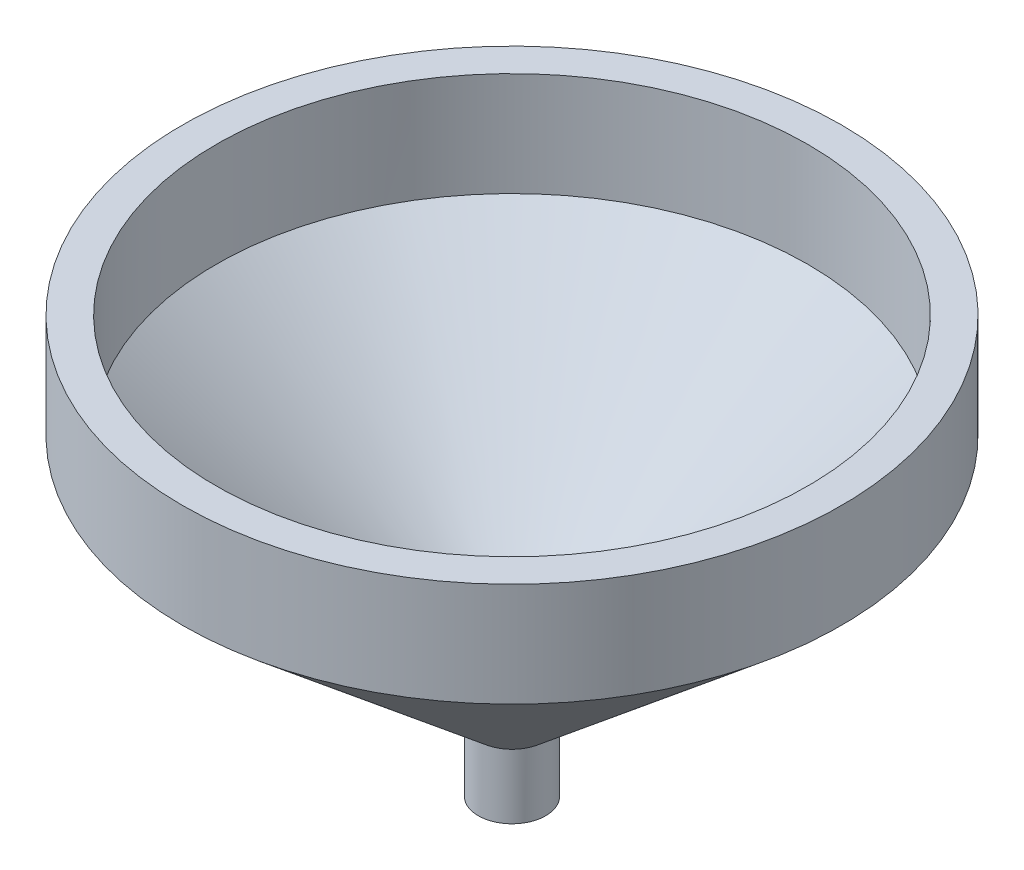
SolidWorks part; units mm, degrees
ref_plane "Front Plane" through (0, 0, 0) normal (0, 0, 1) x (1, 0, 0)
ref_plane "Top Plane" through (0, 0, 0) normal (0, 1, 0) x (1, 0, 0)
ref_plane "Right Plane" through (0, 0, 0) normal (1, 0, 0) x (0, 0, -1)
sketch "Sketch1" plane through (0, 0, 0) normal (1, 0, 0) x (0, 0, -1)
  line L0 (4, 0) -> (4, 6.6869)
  line L1 (4, 6.6869) -> (34.6418, 32.3984)
  line L2 (34.6418, 32.3984) -> (34.6418, 43.1556)
  line L3 (34.6418, 43.1556) -> (38.1306, 43.1556)
  line L4 (38.1306, 43.1556) -> (38.1306, 32.3984)
  line L5 (38.1306, 32.3984) -> (7.4888, 6.6869)
  line L6 (7.4888, 6.6869) -> (7.4888, 0)
  line L7 (7.4888, 0) -> (4, 0)
  dimension "D1" = 4
  dimension "D2" = 50
  dimension "D3" = 40
  dimension "D4" = 40
  dimension "D5" = 6.6869
revolve "Revolve1" add sketch "Sketch1" angle 360 about L0
